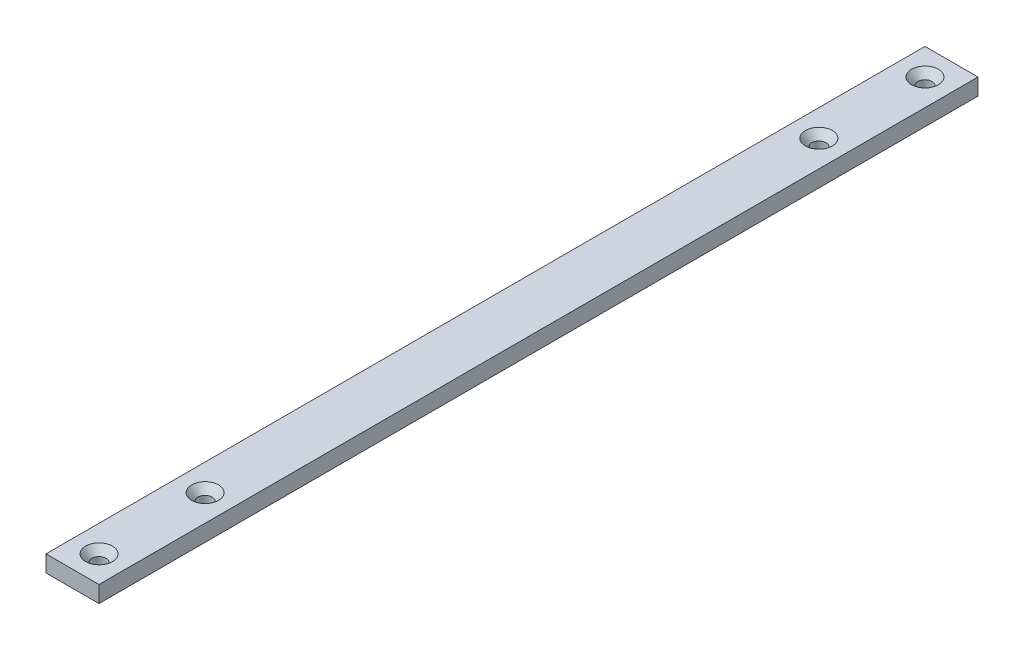
SolidWorks part; units mm, degrees
ref_plane "Front Plane" through (0, 0, 0) normal (0, 0, 1) x (1, 0, 0)
ref_plane "Top Plane" through (0, 0, 0) normal (0, 1, 0) x (1, 0, 0)
ref_plane "Right Plane" through (0, 0, 0) normal (1, 0, 0) x (0, 0, -1)
sketch "Sketch1" plane through (0, 0, 0) normal (0, 0, 1) x (1, 0, 0)
  line L0 (0, 3.9688) -> (0, -3.9688)
  line L1 (-12.7, 0) -> (12.7, 0) construction
  point P6 (0, 0)
  dimension "Width" = 25.4
  dimension "Thk" = 7.9375
sketch "Sketch2" plane through (0, 0, 0) normal (1, 0, 0) x (0, 0, -1)
  line L0 (152.4, 0) -> (-152.4, 0)
  point P4 (0, 0)
  dimension "Length" = 304.8
sketch "Sketch3" plane through (0, 0, 0) normal (0, 0, 1) x (1, 0, 0)
  line L1 (12.7, 3.9688) -> (-12.7, 3.9688)
  line L2 (12.7, 3.9688) -> (12.7, -3.9688)
  line L3 (12.7, -3.9688) -> (-12.7, -3.9688)
  line L4 (-12.7, 3.9688) -> (-12.7, -3.9688)
  line L5 (12.7, 3.9688) -> (-12.7, -3.9688) construction
  line L6 (12.7, -3.9688) -> (-12.7, 3.9688) construction
  point P0 (0, 0)
extrude "Boss-Extrude1" add sketch "Sketch3" along normal mid plane 421
sketch "Sketch5" plane through (0, 3.9688, 0) normal (0, 1, 0) x (1, 0, 0)
  line L0 (12.7, 210.5) -> (-12.7, 210.5) construction
  line L1 (12.7, 210.5) -> (12.7, -210.5) construction
  line L2 (12.7, 0) -> (-12.7, 0) construction
  circle A0 centre (0, 197.8) radius 3.5
  circle A1 centre (0, -197.8) radius 3.5
  circle A2 centre (0, 147) radius 3.5
  circle A3 centre (0, -147) radius 3.5
  dimension "D1" = 7
  dimension "D2" = 12.7
  dimension "D3" = 12.7
  dimension "D4" = 7
  dimension "D5" = 50.8
hole_wizard "CSK for 1/4 Flat Head Machine Screw1" positions "Sketch7" profile "Sketch8" countersink size "1/4" standard "ANSI Inch" end condition through all
sketch "Sketch7" plane through (0, 3.9688, 0) normal (0, 1, 0) x (1, 0, 0)
  point P0 (0, 197.8)
  point P3 (0, -197.8)
  point P6 (0, 147)
  point P9 (0, -147)
sketch "Sketch8" plane through (0, 3.9688, -197.8) normal (1, 0, 0) x (0, 0, 1)
  line L0 (0, 0) -> (0, 7.9375)
  line L1 (0, 7.9375) -> (3.3782, 7.9375)
  line L2 (3.3782, 7.9375) -> (3.3782, 3.5209)
  line L3 (3.3782, 3.5209) -> (6.4389, 0)
  line L5 (6.4389, 0) -> (0, 0)
  line L6 (-3.3782, 3.5209) -> (-6.4389, 0) construction
  line L11 (0, -6.35) -> (0, 107.95) construction
  dimension "Thru Hole Dia." = 6.7564
  dimension "Thru Hole Depth" = 7.9375
  dimension "Near C'Sink Dia." = 12.8778
  dimension "Near C'Sink Angle" = 82
